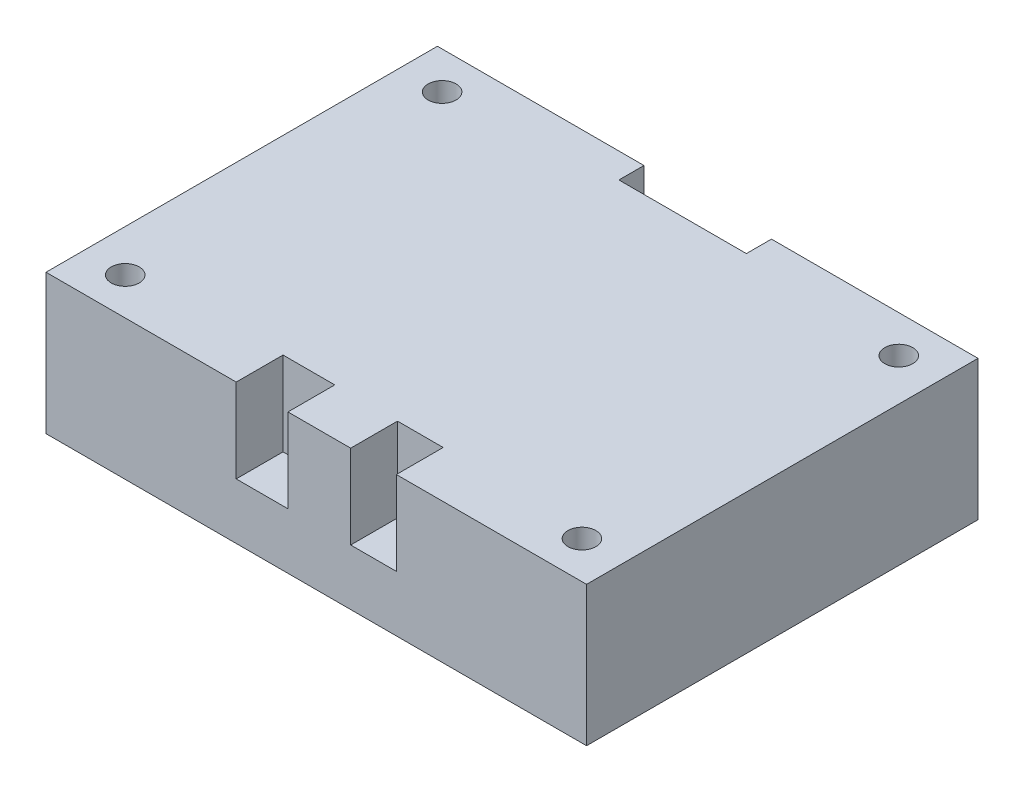
SolidWorks part; units mm, degrees
ref_plane "Front Plane" through (0, 0, 0) normal (0, 0, 1) x (1, 0, 0)
ref_plane "Top Plane" through (0, 0, 0) normal (0, 1, 0) x (1, 0, 0)
ref_plane "Right Plane" through (0, 0, 0) normal (1, 0, 0) x (0, 0, -1)
sketch "草图1" plane through (0, 0, 0) normal (0, 1, 0) x (1, 0, 0)
  line L0 (0, 0) -> (0, 9.4188) construction
  line L1 (-29, 21) -> (29, 21)
  line L2 (-29, 21) -> (-29, -21)
  line L3 (-29, -21) -> (29, -21)
  line L4 (29, 21) -> (29, -21)
  line L5 (-29, 21) -> (29, -21) construction
  line L6 (-29, -21) -> (29, 21) construction
  line L7 (0, 0) -> (-11.4843, 0) construction
  circle A0 centre (-24.5, 17) radius 1.5
  circle A1 centre (-24.5, -17) radius 1.5
  circle A2 centre (24.5, -17) radius 1.5
  circle A3 centre (24.5, 17) radius 1.5
  point P0 (0, 0)
  dimension "D3" = 3
  dimension "D1" = 58
  dimension "D2" = 42
  dimension "D4" = 24.5
  dimension "D5" = 17
extrude "凸台-拉伸1" add sketch "草图1" along normal blind 15
sketch "草图2" plane through (0, 15, 0) normal (0, 1, 0) x (1, 0, 0)
  line L0 (29, 21) -> (-29, 21) construction
  line L1 (-6.8397, 23.6909) -> (6.8397, 23.6909)
  line L2 (-6.8397, 23.6909) -> (-6.8397, 18.3091)
  line L3 (-6.8397, 18.3091) -> (6.8397, 18.3091)
  line L4 (6.8397, 23.6909) -> (6.8397, 18.3091)
  line L5 (-6.8397, 23.6909) -> (6.8397, 18.3091) construction
  line L6 (-6.8397, 18.3091) -> (6.8397, 23.6909) construction
  point P0 (0, 21)
extrude "切除-拉伸1" cut sketch "草图2" against normal blind 12
sketch "草图3" plane through (0, 15, 0) normal (0, 1, 0) x (1, 0, 0)
  line L0 (-29, -21) -> (29, -21) construction
  line L1 (-8.5913, -15.9759) -> (8.5913, -15.9759)
  line L2 (-8.5913, -15.9759) -> (-8.5913, -26.0241)
  line L3 (-8.5913, -26.0241) -> (8.5913, -26.0241)
  line L4 (8.5913, -15.9759) -> (8.5913, -26.0241)
  line L5 (-8.5913, -15.9759) -> (8.5913, -26.0241) construction
  line L6 (-8.5913, -26.0241) -> (8.5913, -15.9759) construction
  point P0 (0, -21)
extrude "切除-拉伸2" cut sketch "草图3" against normal blind 9
sketch "草图4" plane through (0, 6, 0) normal (0, 1, 0) x (1, 0, 0)
  line L0 (8.5913, -15.9759) -> (-8.5913, -15.9759) construction
  line L1 (-3.0393, -15.9759) -> (3.6906, -15.9759)
  line L2 (-3.0393, -15.9759) -> (-3.0393, -21)
  line L3 (-3.0393, -21) -> (3.6906, -21)
  line L4 (3.6906, -15.9759) -> (3.6906, -21)
  line L5 (-8.5913, -21) -> (8.5913, -21) construction
extrude "凸台-拉伸2" add sketch "草图4" along normal blind 9
